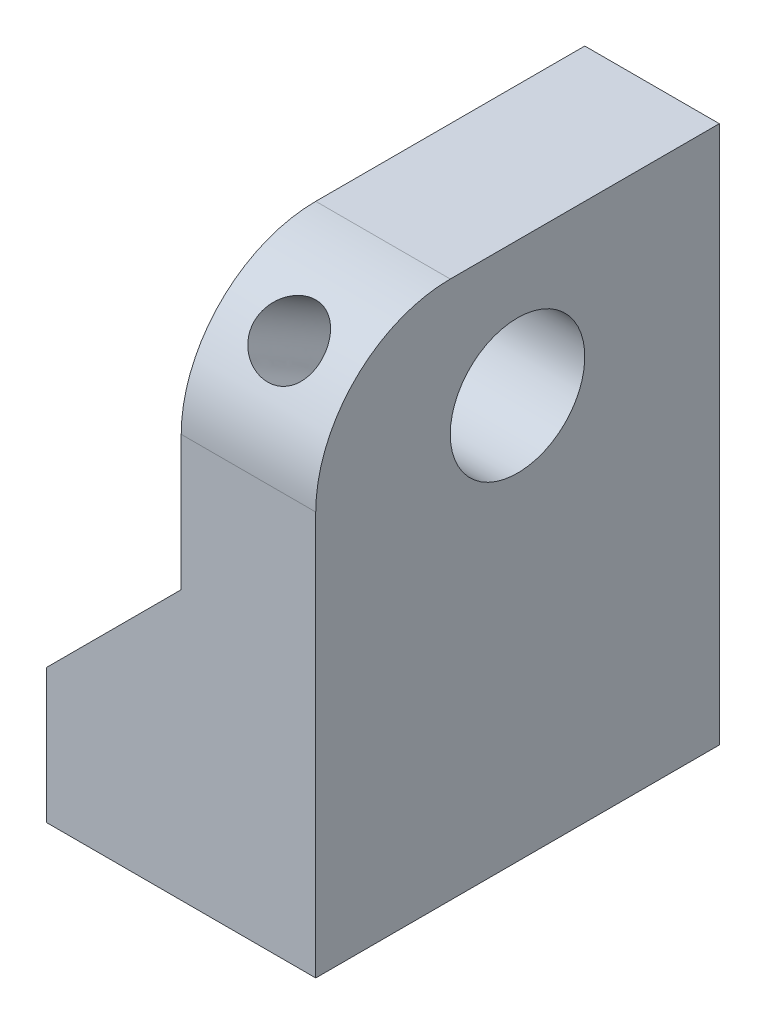
SolidWorks part; units mm, degrees
ref_plane "Front Plane" through (0, 0, 0) normal (0, 0, 1) x (1, 0, 0)
ref_plane "Top Plane" through (0, 0, 0) normal (0, 1, 0) x (1, 0, 0)
ref_plane "Right Plane" through (0, 0, 0) normal (1, 0, 0) x (0, 0, -1)
sketch "Sketch1" plane through (0, 0, 0) normal (0, 0, 1) x (1, 0, 0)
  line L0 (0, 0) -> (50.8, 0)
  line L1 (50.8, 0) -> (50.8, 101.6)
  line L2 (50.8, 101.6) -> (25.4, 101.6)
  line L3 (25.4, 101.6) -> (25.4, 50.8)
  line L4 (25.4, 50.8) -> (0, 25.4)
  line L5 (0, 25.4) -> (0, 0)
  dimension "D1" = 25.4
  dimension "D2" = 25.4
  dimension "D3" = 101.6
  dimension "D4" = 50.8
  dimension "D5" = 25.4
extrude "Boss-Extrude1" add sketch "Sketch1" along normal blind 76.2
fillet "Fillet1" radius 25.4 1 edges at (38.1, 101.6, 76.2)
sketch "Sketch2" plane through (0, 0, 0) normal (1, 0, 0) x (0, 0, -1)
  line L0 (0, 76.2) -> (-38.1, 76.2) construction
  line L1 (0, 101.6) -> (0, 50.8) construction
  line L2 (-38.1, 76.2) -> (-38.1, 101.6) construction
  line L3 (-50.8, 101.6) -> (0, 101.6) construction
  circle A0 centre (-38.1, 76.2) radius 12.7
  dimension "D3" = 25.4
  dimension "D1" = 38.1
  dimension "D2" = 25.4
extrude "Cut-Extrude1" cut sketch "Sketch2" against normal mid plane 504.952
ref_plane "Plane1" through (38.1, 0, 0) normal (-1, 0, 0) x (0, 0, 1)
ref_point "Point2"
ref_plane "Plane3" through (38.1, 94.1605, 68.7605) normal (0, 0.7071, 0.7071) x (1, 0, 0)
sketch "Sketch4" plane through (38.1, 0, -38.1) normal (-1, 0, 0) x (0, 0, 1)
  line L0 (76.2, 76.2) -> (106.8605, 94.1605)
  arc A1 (114.3, 76.2) -> (88.9, 101.6) centre (88.9, 76.2) ccw construction
sketch "Sketch7" plane through (38.1, 94.1605, 68.7605) normal (0, 0.7071, 0.7071) x (1, 0, 0)
  circle A0 centre (0, 0) radius 6.35
  dimension "D1" = 12.7
sweep "Cut-Sweep1" cut profiles "Sketch7" path "Sketch4"
